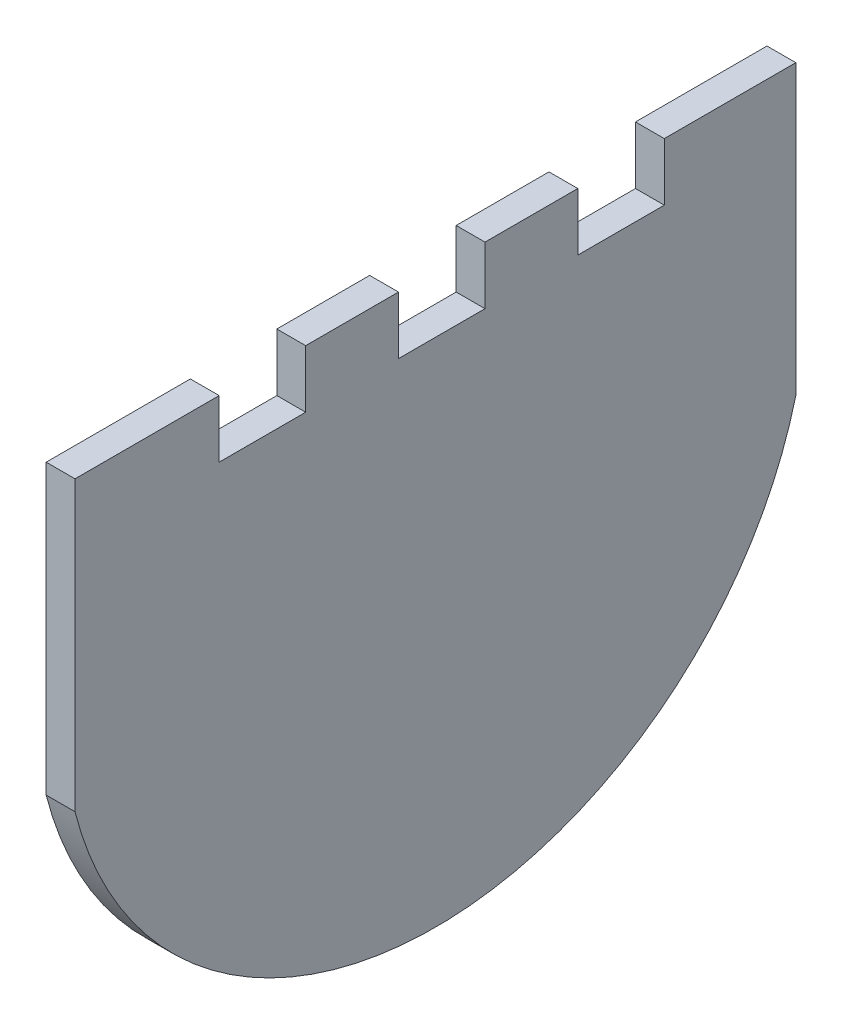
SolidWorks part; units mm, degrees
ref_plane "Front Plane" through (0, 0, 0) normal (0, 0, 1) x (1, 0, 0)
ref_plane "Top Plane" through (0, 0, 0) normal (0, 1, 0) x (1, 0, 0)
ref_plane "Right Plane" through (0, 0, 0) normal (1, 0, 0) x (0, 0, -1)
sketch "Sketch1" plane through (0, 0, 0) normal (1, 0, 0) x (0, 0, -1)
  line L0 (0, 55) -> (0, -55) construction
  line L1 (-31.75, 33.3763) -> (-31.75, 7.9763)
  line L2 (0, 33.3763) -> (31.75, 33.3763)
  line L3 (0, 33.3763) -> (-31.75, 33.3763)
  line L4 (31.75, 33.3763) -> (31.75, 7.9763)
  line L5 (-31.75, 7.9763) -> (31.75, 7.9763)
  arc A0 (31.75, 7.9763) -> (-31.75, 7.9763) centre (0, 16.0398) cw
  dimension "D1" = 63.5
  dimension "D2" = 25.4
extrude "Boss-Extrude2" add sketch "Sketch1" along normal blind 2.54 contours L1 L5 L4 L2 L3 | A0 L5
sketch "Sketch3" plane through (0, 33.3763, 0) normal (0, 1, 0) x (1, 0, 0)
  line L0 (0, -19.05) -> (2.54, -19.05)
  line L1 (0, -31.75) -> (0, 31.75) construction
  line L2 (2.54, -31.75) -> (2.54, 31.75) construction
  line L3 (2.54, -19.05) -> (2.54, -11.43)
  line L4 (2.54, -11.43) -> (0, -11.43)
  line L5 (0, -11.43) -> (0, -19.05)
  line L6 (0, -3.2529) -> (2.54, -3.2529)
  line L7 (2.54, -3.2529) -> (2.54, 4.3671)
  line L8 (2.54, 4.3671) -> (0, 4.3671)
  line L9 (0, 4.3671) -> (0, -3.2529)
  line L10 (0, 12.5442) -> (2.54, 12.5442)
  line L11 (2.54, 12.5442) -> (2.54, 20.1642)
  line L12 (2.54, 20.1642) -> (0, 20.1642)
  line L13 (0, 20.1642) -> (0, 12.5442)
  line L14 (2.54, -31.75) -> (0, -31.75) construction
  line L15 (2.54, 31.75) -> (0, 31.75) construction
  point P14 (1.27, -31.75)
  point P19 (1.27, 31.75)
  point P22 (1.27, -31.75)
  point P23 (-17.6823, -72.4508)
  dimension "D1" = 63.5
extrude "Cut-Extrude2" cut sketch "Sketch3" against normal blind 5.08
equation "\"D3@Sketch3\" = 2.5/6"
equation "\"D4@Sketch3\" = 2.5/6"
equation "\"D2@Sketch3\" = 2.5/6"
